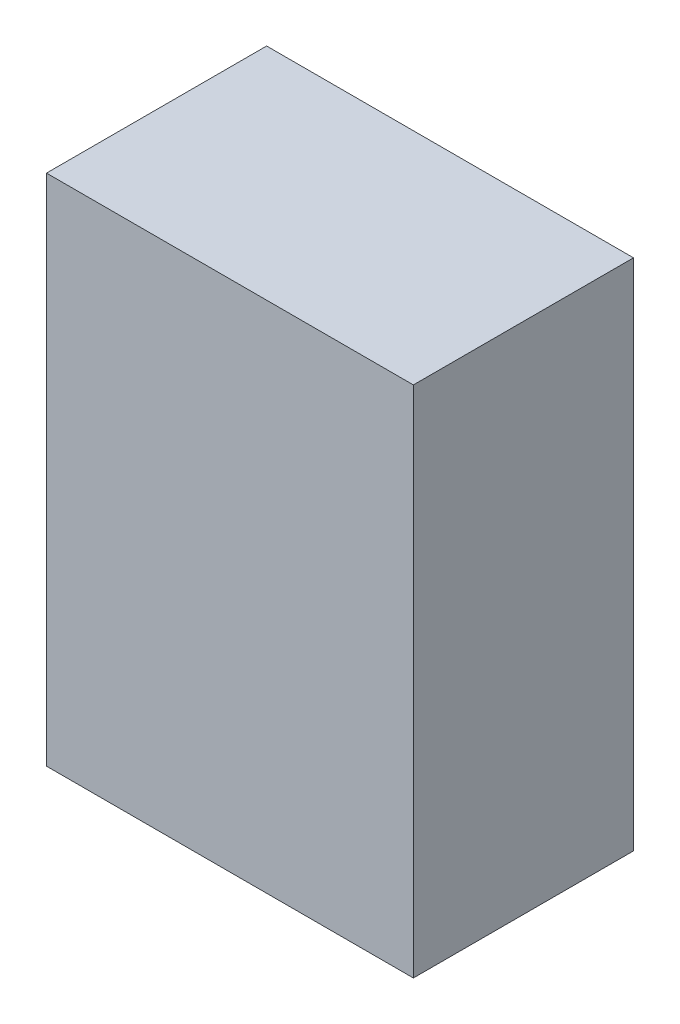
SolidWorks part; units mm, degrees
ref_plane "Front Plane" through (0, 0, 0) normal (1, 0, 0) x (0, 1, 0)
ref_plane "Top Plane" through (0, 0, 0) normal (0, 0, 1) x (0, 1, 0)
ref_plane "Right Plane" through (0, 0, 0) normal (0, 1, 0) x (-1, 0, 0)
sketch "Sketch1" plane through (0, 0, 0) normal (0, 0, 1) x (0, 1, 0)
  line L1 (0, 0) -> (70, 0)
  line L2 (0, 0) -> (0, 50)
  line L3 (0, 50) -> (70, 50)
  line L4 (70, 0) -> (70, 50)
  dimension "D1" = 70
  dimension "D2" = 50
extrude "Boss-Extrude1" add sketch "Sketch1" along normal blind 30
